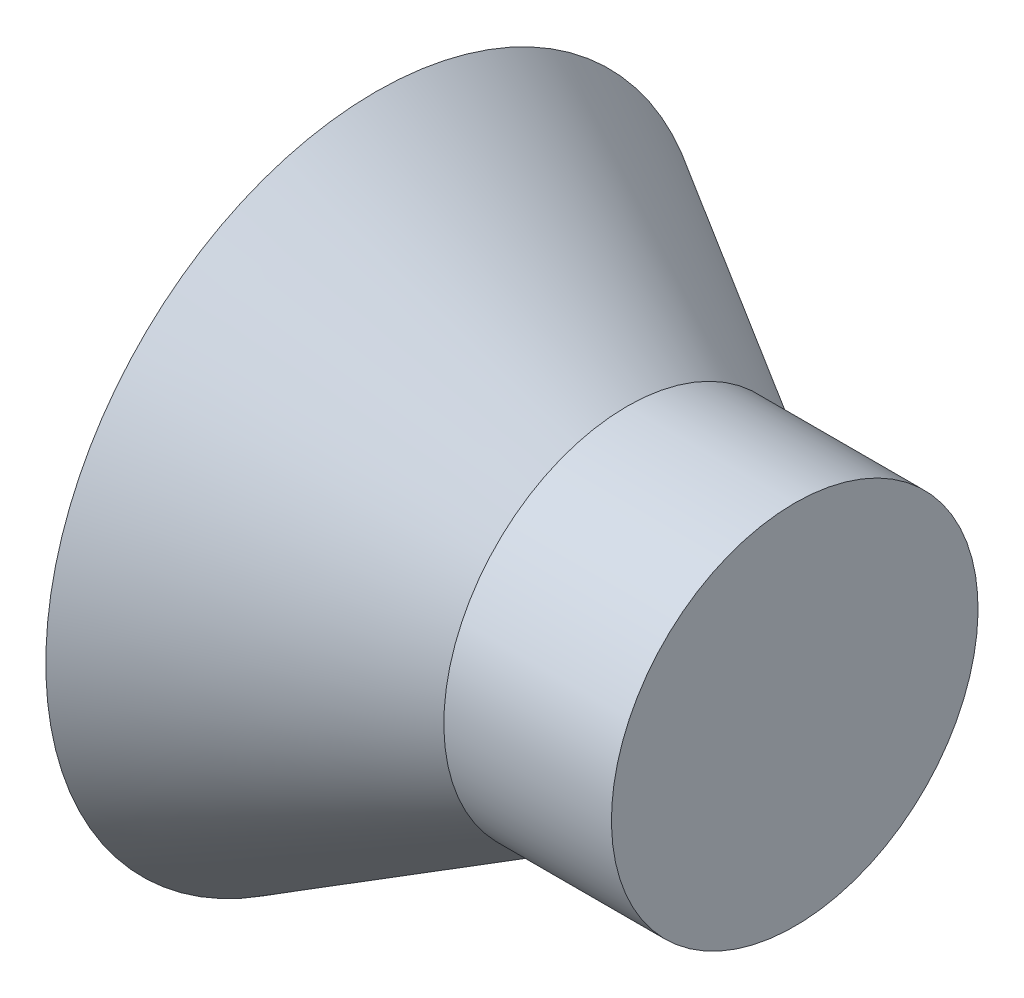
SolidWorks part; units mm, degrees
material "碳钢"
ref_plane "前视基准面" through (0, 0, 0) normal (0, 0, 1) x (1, 0, 0)
ref_plane "上视基准面" through (0, 0, 0) normal (0, 1, 0) x (1, 0, 0)
ref_plane "右视基准面" through (0, 0, 0) normal (1, 0, 0) x (0, 0, -1)
sketch "草图1" plane through (0, 0, 0) normal (0, 0, 1) x (1, 0, 0)
  line L0 (0, 0) -> (0, 3.15)
  line L1 (0, 3.15) -> (2.4, 1.75)
  line L2 (2.4, 1.75) -> (4, 1.75)
  line L3 (4, 1.75) -> (4, 0)
  line L4 (4, 0) -> (0, 0) construction
  line L5 (0, 0) -> (4, 0)
  dimension "D1" = 3.5
  dimension "D2" = 4
  dimension "D3" = 6.3
  dimension "D4" = 2.4
revolve "旋转1" add sketch "草图1" angle 360 about L4
cosmetic thread "装饰螺纹线1" parameters "D2"=2.85
sketch "草图2" plane through (0, 0, 0) normal (-1, 0, 0) x (0, 0, 1)
  line L1 (-2, -0.4) -> (2, -0.4)
  line L2 (-2, -0.4) -> (-2, 0.4)
  line L3 (-2, 0.4) -> (2, 0.4)
  line L4 (2, -0.4) -> (2, 0.4)
  line L5 (0, 0.4) -> (0, -0.4) construction
  line L6 (-2, 0) -> (2, 0) construction
  line L7 (-0.4, -2) -> (0.4, -2)
  line L8 (-0.4, -2) -> (-0.4, 2)
  line L9 (-0.4, 2) -> (0.4, 2)
  line L10 (0.4, -2) -> (0.4, 2)
  line L11 (0, 2) -> (0, -2) construction
  line L12 (-0.4, 0) -> (0.4, 0) construction
  point P0 (0, 0)
  point P4 (0, 0)
  dimension "D1" = 0.8
  dimension "D2" = 4
extrude "切除-拉伸1" cut sketch "草图2" against normal blind 0.5 contours L7 L10 L1 L8 | L10 L1 L4 L3 | L3 L10 L9 L8 | L1 L10 L3 L8 | L1 L8 L3 L2
